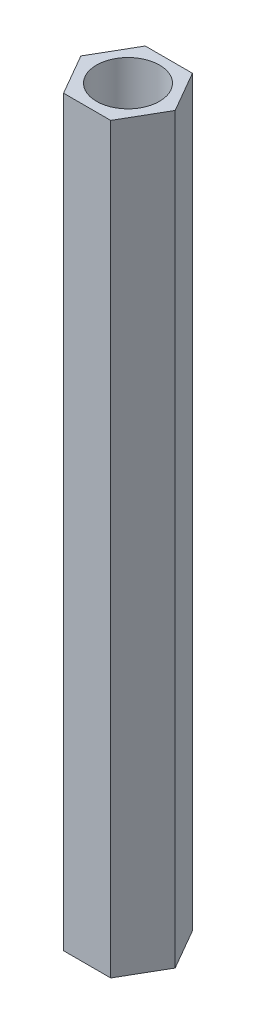
SolidWorks part; units mm, degrees
ref_plane "Front Plane" through (0, 0, 0) normal (0, 0, 1) x (1, 0, 0)
ref_plane "Top Plane" through (0, 0, 0) normal (0, 1, 0) x (1, 0, 0)
ref_plane "Right Plane" through (0, 0, 0) normal (1, 0, 0) x (0, 0, -1)
sketch "Sketch1" plane through (0, 0, 0) normal (0, 1, 0) x (1, 0, 0)
  line L1 (1.9053, 0) -> (0.9526, 1.65)
  line L2 (0.9526, 1.65) -> (-0.9526, 1.65)
  line L3 (-0.9526, 1.65) -> (-1.9053, 0)
  line L4 (-1.9053, 0) -> (-0.9526, -1.65)
  line L5 (-0.9526, -1.65) -> (0.9526, -1.65)
  line L6 (0.9526, -1.65) -> (1.9053, 0)
  circle A0 centre (0, 0) radius 1.65 construction
  dimension "D1" = 3.3
extrude "Boss-Extrude1" add sketch "Sketch1" along normal blind 30
sketch "Sketch2" plane through (0, 30, 0) normal (0, 1, 0) x (1, 0, 0)
  circle A0 centre (0, 0) radius 1.2716
extrude "Cut-Extrude1" cut sketch "Sketch2" against normal blind 30
